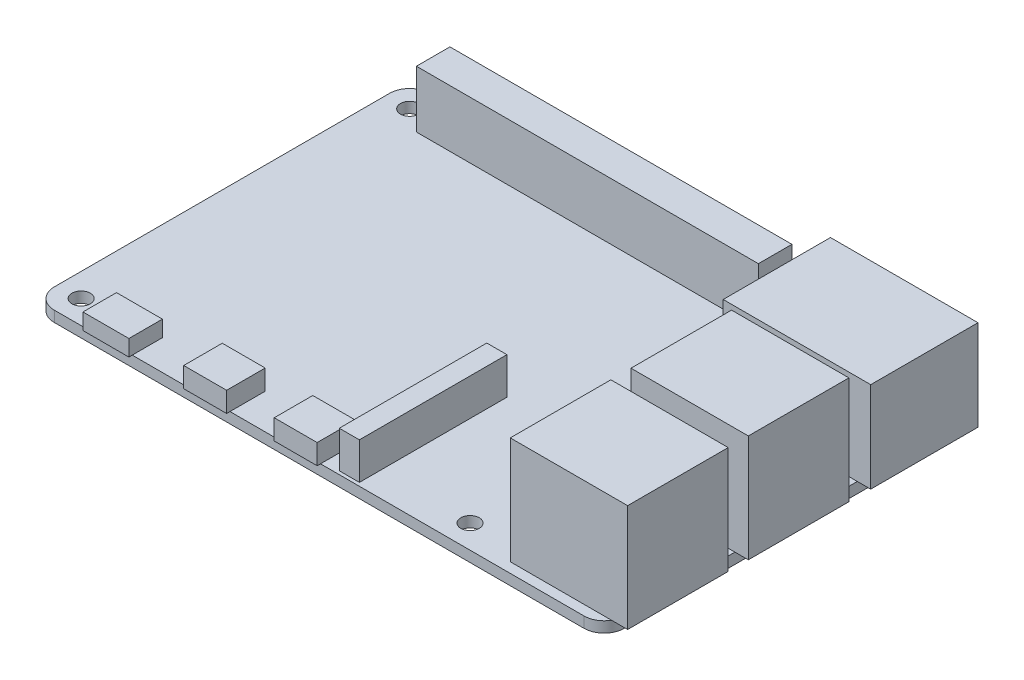
SolidWorks part; units mm, degrees
ref_plane "Front Plane" through (0, 0, 0) normal (0, 0, 1) x (1, 0, 0)
ref_plane "Top Plane" through (0, 0, 0) normal (0, 1, 0) x (1, 0, 0)
ref_plane "Right Plane" through (0, 0, 0) normal (1, 0, 0) x (0, 0, -1)
sketch "Sketch2" plane through (0, 0, 0) normal (0, 1, 0) x (1, 0, 0)
  line L1 (3, 0) -> (82, 0)
  line L2 (0, 3) -> (0, 53)
  line L3 (3, 56) -> (82, 56)
  line L4 (85, 3) -> (85, 53)
  arc A0 (3, 0) -> (0, 3) centre (3, 3) cw
  arc A1 (82, 0) -> (85, 3) centre (82, 3) ccw
  arc A2 (82, 56) -> (85, 53) centre (82, 53) cw
  arc A3 (0, 53) -> (3, 56) centre (3, 53) cw
  point P7 (0, 0)
  point P10 (85, 0)
  point P15 (0, 56)
  dimension "D3" = 3
  dimension "D1" = 56
  dimension "D2" = 85
extrude "Main Board" add sketch "Sketch2" along normal blind 1.6
sketch "Sketch3" plane through (0, 0, 0) normal (0, 1, 0) x (1, 0, 0)
  line L0 (0, 53) -> (0, 3) construction
  line L1 (3, 0) -> (82, 0) construction
  line L2 (82, 56) -> (3, 56) construction
  circle A0 centre (3.5, 3.5) radius 1.375
  circle A1 centre (3.5, 52.5) radius 1.375
  circle A2 centre (61.5, 52.5) radius 1.375
  circle A3 centre (61.5, 3.5) radius 1.375
  dimension "D7" = 2.75
  dimension "D8" = 2.75
  dimension "D9" = 2.75
  dimension "D10" = 2.75
  dimension "D1" = 3.5
  dimension "D2" = 3.5
  dimension "D3" = 3.5
  dimension "D4" = 3.5
  dimension "D5" = 58
  dimension "D6" = 58
  dimension "D11" = 3.5
  dimension "D12" = 3.5
extrude "Board Holes" cut sketch "Sketch3" along normal up to body
sketch "MicroUSB PWR" plane through (0, 1.6, 0) normal (0, 1, 0) x (1, 0, 0)
  line L1 (7.775, -0.5) -> (14.625, -0.5)
  line L2 (7.775, -0.5) -> (7.775, 4.5)
  line L3 (7.775, 4.5) -> (14.625, 4.5)
  line L4 (14.625, -0.5) -> (14.625, 4.5)
  line L5 (7.775, -0.5) -> (14.625, 4.5) construction
  line L6 (7.775, 4.5) -> (14.625, -0.5) construction
  line L8 (3, 0) -> (82, 0) construction
  circle A0 centre (3.5, 3.5) radius 1.375 construction
  point P0 (11.2, 2)
  dimension "D1" = 7.7
  dimension "D2" = 6.85
  dimension "D3" = 0.5
  dimension "D4" = 5
extrude "USB C" add sketch "MicroUSB PWR" along normal blind 2.4 separate body
sketch "Sketch5" plane through (0, 1.6, 0) normal (0, 1, 0) x (1, 0, 0)
  line L1 (22.8, -0.5) -> (29.2, -0.5)
  line L2 (22.8, -0.5) -> (22.8, 5.2504)
  line L3 (22.8, 5.2504) -> (29.2, 5.2504)
  line L4 (29.2, -0.5) -> (29.2, 5.2504)
  line L5 (22.8, -0.5) -> (29.2, 5.2504) construction
  line L6 (22.8, 5.2504) -> (29.2, -0.5) construction
  line L7 (14.625, 0) -> (82, 0) construction
  line L8 (7.775, -0.5) -> (14.625, -0.5) construction
  line L10 (36.3, 5.2504) -> (42.7, 5.2504)
  line L11 (36.3, 5.2504) -> (36.3, -0.5)
  line L12 (36.3, -0.5) -> (42.7, -0.5)
  line L13 (42.7, 5.2504) -> (42.7, -0.5)
  line L14 (36.3, 5.2504) -> (42.7, -0.5) construction
  line L15 (36.3, -0.5) -> (42.7, 5.2504) construction
  point P0 (26, 2.3752)
  point P7 (11.2, -0.5)
  point P10 (39.5, 2.3752)
  dimension "D1" = 14.8
  dimension "D2" = 0.5
  dimension "D3" = 6.4
  dimension "D4" = 13.5
extrude "MicroHDMIs" add sketch "Sketch5" along normal blind 3
sketch "Sketch6" plane through (0, 1.6, 0) normal (0, 1, 0) x (1, 0, 0)
  line L1 (45, 0.5) -> (48, 0.5)
  line L2 (45, 0.5) -> (45, 22.5)
  line L3 (45, 22.5) -> (48, 22.5)
  line L4 (48, 0.5) -> (48, 22.5)
  line L5 (45, 0.5) -> (48, 22.5) construction
  line L6 (45, 22.5) -> (48, 0.5) construction
  line L7 (29.2, 0) -> (36.3, 0) construction
  line L8 (36.3, -0.5) -> (42.7, -0.5) construction
  point P0 (46.5, 11.5)
  point P8 (39.5, -0.5)
  dimension "D1" = 7
  dimension "D2" = 0.5
  dimension "D3" = 11.5
  dimension "D4" = 3
extrude "Camera Port" add sketch "Sketch6" along normal blind 5.5
sketch "Sketch7" plane through (0, 1.6, 0) normal (0, 1, 0) x (1, 0, 0)
  line L0 (29.2, 0) -> (36.3, 0) construction
  line L1 (65, 37.75) -> (87, 37.75)
  line L2 (65, 37.75) -> (65, 53.75)
  line L3 (65, 53.75) -> (87, 53.75)
  line L4 (87, 37.75) -> (87, 53.75)
  line L5 (65, 37.75) -> (87, 53.75) construction
  line L6 (65, 53.75) -> (87, 37.75) construction
  line L7 (85, 3) -> (85, 53) construction
  point P0 (76, 45.75)
  dimension "D1" = 45.75
  dimension "D2" = 16
  dimension "D3" = 22
  dimension "D4" = 2
extrude "Ethernet port" add sketch "Sketch7" along normal blind 13.5
sketch "Sketch8" plane through (0, 1.6, 0) normal (0, 1, 0) x (1, 0, 0)
  line L0 (29.2, 0) -> (36.3, 0) construction
  line L1 (69.5, 1.5) -> (87, 1.5)
  line L2 (69.5, 1.5) -> (69.5, 16.5)
  line L3 (69.5, 16.5) -> (87, 16.5)
  line L4 (87, 1.5) -> (87, 16.5)
  line L5 (69.5, 1.5) -> (87, 16.5) construction
  line L6 (69.5, 16.5) -> (87, 1.5) construction
  line L7 (85, 3) -> (85, 37.75) construction
  point P0 (78.25, 9)
  dimension "D1" = 9
  dimension "D2" = 17.5
  dimension "D3" = 15
  dimension "D4" = 2
sketch "Sketch9" plane through (0, 1.6, 1.6) normal (0, 1, 0) x (1, 0, 0)
  line L0 (29.2, 1.6) -> (36.3, 1.6) construction
  line L1 (69.5, 21.1) -> (87, 21.1)
  line L2 (69.5, 21.1) -> (69.5, 36.1)
  line L3 (69.5, 36.1) -> (87, 36.1)
  line L4 (87, 21.1) -> (87, 36.1)
  line L5 (69.5, 21.1) -> (87, 36.1) construction
  line L6 (69.5, 36.1) -> (87, 21.1) construction
  line L7 (85, 4.6) -> (85, 39.35) construction
  point P0 (78.25, 28.6)
  dimension "D1" = 27
  dimension "D2" = 17.5
  dimension "D3" = 15
  dimension "D4" = 2
extrude "USB 1" add sketch "Sketch8" along normal blind 16
extrude "USB 2" add sketch "Sketch9" along normal blind 16
sketch "Sketch10" plane through (0, 1.6, 0) normal (0, 1, 0) x (1, 0, 0)
  line L1 (7, 50) -> (58, 50)
  line L2 (7, 50) -> (7, 55)
  line L3 (7, 55) -> (58, 55)
  line L4 (58, 50) -> (58, 55)
  line L5 (7, 50) -> (58, 55) construction
  line L6 (7, 55) -> (58, 50) construction
  line L7 (82, 56) -> (3, 56) construction
  circle A0 centre (3.5, 52.5) radius 1.375 construction
  point P0 (32.5, 52.5)
  dimension "D1" = 29
  dimension "D2" = 5
  dimension "D3" = 51
  dimension "D4" = 1
extrude "GPIO" add sketch "Sketch10" along normal blind 8.5
sketch "Sketch11" plane through (0, 0, 0) normal (0, -1, 0) x (1, 0, 0)
  line L1 (6, -22.25) -> (12, -22.25)
  line L2 (6, -22.25) -> (6, -33.75)
  line L3 (6, -33.75) -> (12, -33.75)
  line L4 (12, -22.25) -> (12, -33.75)
  line L5 (6, -22.25) -> (12, -33.75) construction
  line L6 (6, -33.75) -> (12, -22.25) construction
  line L7 (0, -53) -> (0, -3) construction
  line L8 (0, -28) -> (85, -28) construction
  line L9 (85, -3) -> (85, -53) construction
  point P0 (9, -28)
  dimension "D1" = 12
  dimension "D2" = 11.5
  dimension "D3" = 6
extrude "Boss-Extrude1" add sketch "Sketch11" along normal blind 1.125
equation "\"HoleRadius\"= 2.75"
equation "\"D7@Sketch3\"=\"HoleRadius\""
equation "\"D8@Sketch3\"=\"HoleRadius\""
equation "\"D9@Sketch3\"=\"HoleRadius\""
equation "\"D10@Sketch3\"=\"HoleRadius\""
